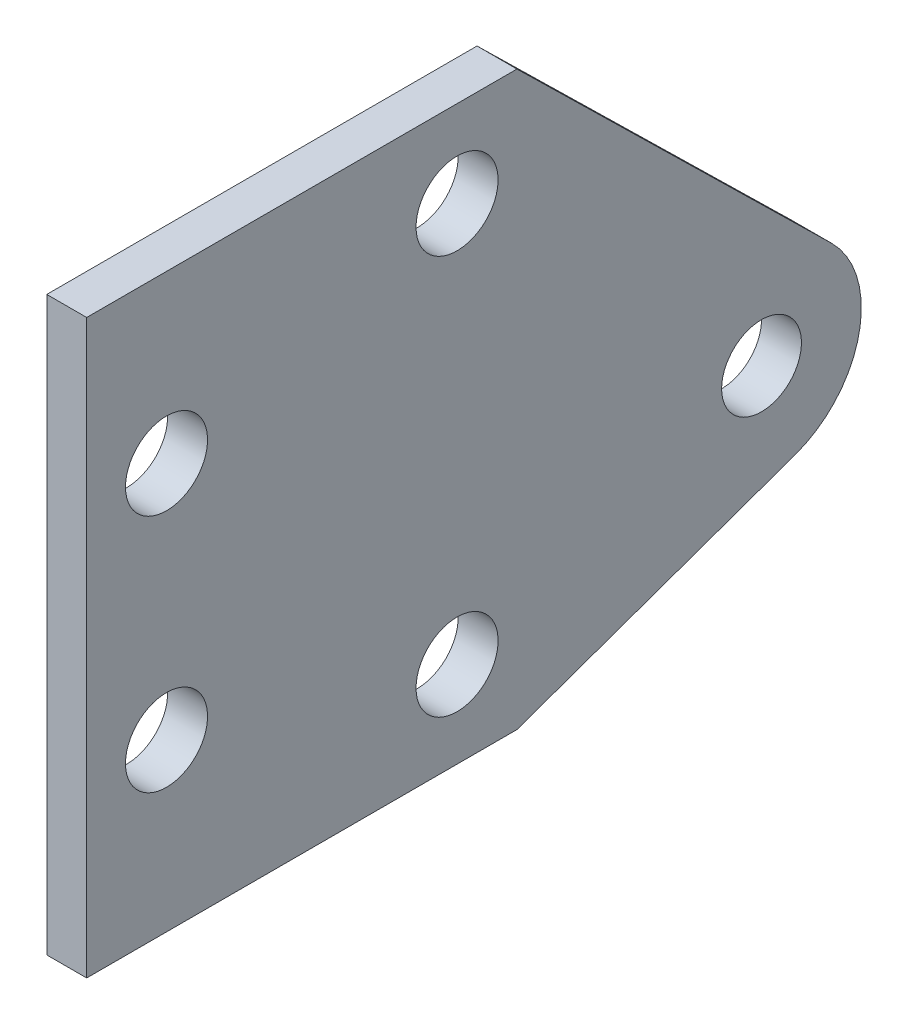
SolidWorks part; units mm, degrees
ref_plane "Front Plane" through (0, 0, 0) normal (0, 0, 1) x (1, 0, 0)
ref_plane "Top Plane" through (0, 0, 0) normal (0, 1, 0) x (1, 0, 0)
ref_plane "Right Plane" through (0, 0, 0) normal (1, 0, 0) x (0, 0, -1)
sketch "Sketch1" plane through (-25.4, 0, 0) normal (-1, 0, 0) x (0, 0, 1)
  line L6 (-88.4975, 379.3607) -> (-113.504, 354.8689) construction
  line L9 (-88.4975, 379.3607) -> (-113.504, 354.8689)
  line L24 (-103.0725, 379.3607) -> (-103.0725, 365.0857)
  line L25 (-103.0725, 379.3607) -> (-103.0725, 365.0857)
  line L26 (-54.275, 379.3607) -> (-103.0725, 379.3607)
  line L27 (-103.0725, 365.0857) -> (-113.504, 354.8689)
  line L28 (-110.6082, 341.719) -> (-88.4975, 333.8607)
  line L29 (-88.4975, 333.8607) -> (-54.275, 333.8607)
  line L30 (-54.275, 333.8607) -> (-54.275, 379.3607)
  line L31 (-54.275, 379.3607) -> (-103.0725, 379.3607)
  line L32 (-103.0725, 365.0857) -> (-113.504, 354.8689)
  line L33 (-110.6082, 341.719) -> (-88.4975, 333.8607)
  line L34 (-88.4975, 333.8607) -> (-54.275, 333.8607)
  line L35 (-54.275, 333.8607) -> (-54.275, 379.3607)
  circle A1 centre (-83.735, 372.4857) radius 2.3813 construction
  circle A2 centre (-83.735, 340.7357) radius 2.3813 construction
  circle A3 centre (-60.625, 366.1357) radius 2.3813 construction
  circle A4 centre (-60.625, 347.0857) radius 2.3813 construction
  circle A6 centre (-83.735, 372.4857) radius 2.3813
  circle A7 centre (-83.735, 340.7357) radius 2.3813
  circle A8 centre (-60.625, 366.1357) radius 2.3813
  circle A9 centre (-60.625, 347.0857) radius 2.3813
  circle A13 centre (-107.95, 349.1982) radius 3.175
  circle A14 centre (-107.95, 349.1982) radius 3.175
  arc A15 (-113.504, 354.8689) -> (-110.6082, 341.719) centre (-107.95, 349.1982) ccw
  arc A16 (-113.504, 354.8689) -> (-110.6082, 341.719) centre (-107.95, 349.1982) ccw
  circle M7 centre (-60.625, 347.0857) radius 3.2639
  circle M8 centre (-83.735, 340.7357) radius 3.2639
  line M9 (-54.275, 379.3607) -> (-88.4975, 379.3607)
  line M10 (-88.4975, 379.3607) -> (-102.0374, 362.628)
  arc M11 (-102.0374, 362.628) -> (-102.1959, 351.8452) centre (-95.25, 357.1357) ccw
  line M12 (-102.1959, 351.8452) -> (-88.4975, 333.8607)
  line M13 (-88.4975, 333.8607) -> (-54.275, 333.8607)
  line M14 (-54.275, 333.8607) -> (-54.275, 379.3607)
  circle M15 centre (-95.25, 357.1357) radius 3.9687
  circle M16 centre (-83.735, 372.4857) radius 3.2639
  circle M17 centre (-60.625, 366.1357) radius 3.2639
  dimension "D1" = 0
  dimension "D2" = 0
extrude "Boss-Extrude1" add sketch "Sketch1" along normal blind 3.175 contours L9 A16 L33 A14 M12 M11 M10 | M14 M9 M10 M11 M12 M13 M8 M15 M17 M16 M7 | M15
